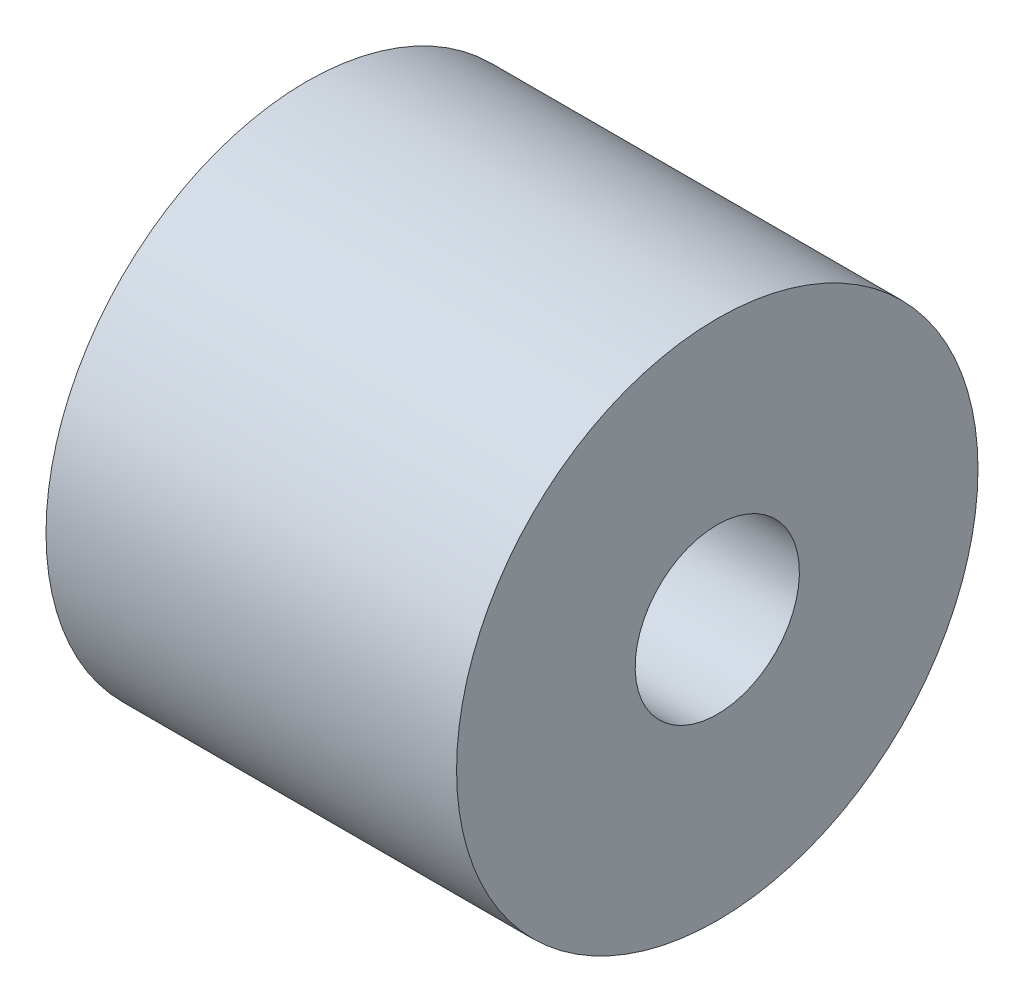
SolidWorks part; units mm, degrees
ref_plane "Plan de face" through (0, 0, 0) normal (0, 0, 1) x (1, 0, 0)
ref_plane "Plan de dessus" through (0, 0, 0) normal (0, 1, 0) x (1, 0, 0)
ref_plane "Plan de droite" through (0, 0, 0) normal (1, 0, 0) x (0, 0, -1)
sketch "Esquisse1" plane through (-130.4032, 0, 0) normal (1, 0, 0) x (0, 0, -1)
  circle A0 centre (-120.9082, 39.0096) radius 6.35
  circle A1 centre (-120.9082, 39.0096) radius 2
  dimension "D1" = 12.7
  dimension "D2" = 4
extrude "Boss.-Extru.1" add sketch "Esquisse1" against normal blind 10
